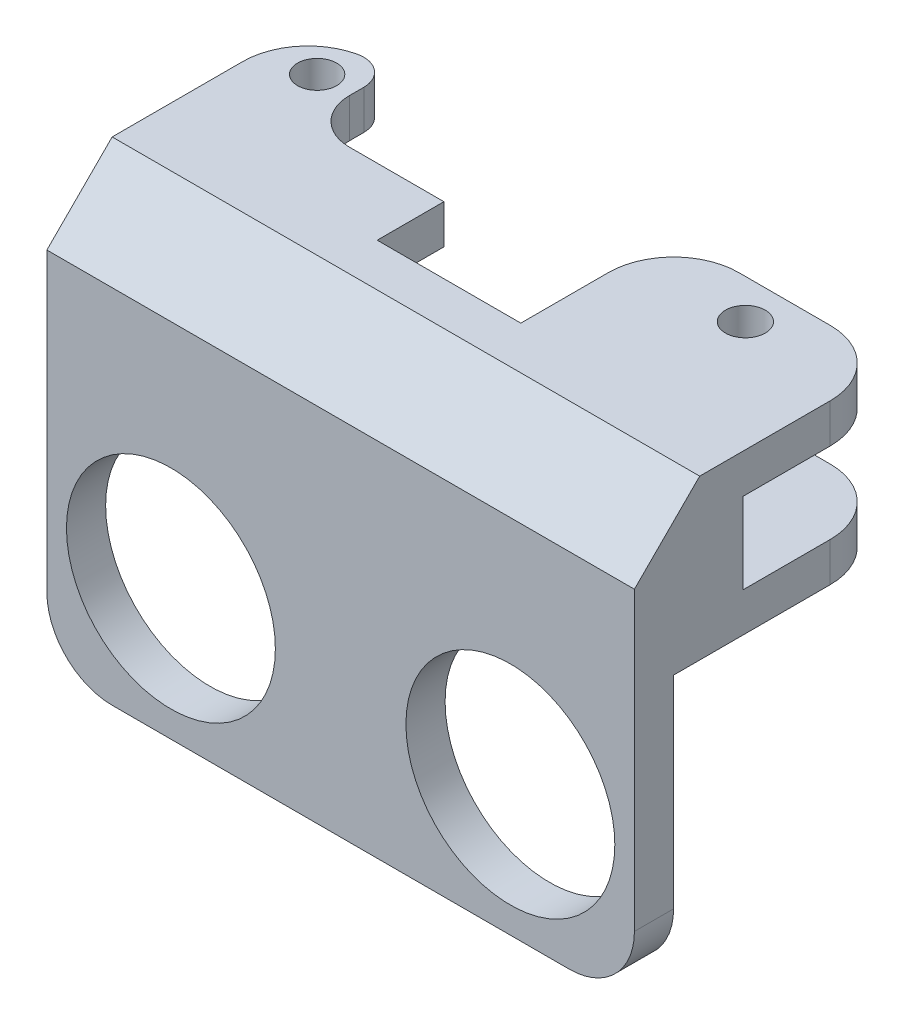
SolidWorks part; units mm, degrees
ref_plane "Front Plane" through (0, 0, 0) normal (0, 0, 1) x (1, 0, 0)
ref_plane "Top Plane" through (0, 0, 0) normal (0, 1, 0) x (1, 0, 0)
ref_plane "Right Plane" through (0, 0, 0) normal (1, 0, 0) x (0, 0, -1)
sketch "Sketch1" plane through (0, 0, 0) normal (0, 0, 1) x (1, 0, 0)
  line L0 (-17.5, -10.5) -> (17.5, -10.5)
  line L1 (22.5, -5.5) -> (22.5, 10.5)
  line L3 (-22.5, 10.5) -> (-22.5, -5.5)
  line L6 (-22.5, 10.5) -> (-22.5, 13)
  line L7 (-22.5, 13) -> (22.5, 13)
  line L8 (22.5, 10.5) -> (22.5, 13)
  circle A0 centre (13, -0.5) radius 8
  circle A1 centre (-13, -0.5) radius 8
  arc A2 (17.5, -10.5) -> (22.5, -5.5) centre (17.5, -5.5) ccw
  arc A3 (-22.5, -5.5) -> (-17.5, -10.5) centre (-17.5, -5.5) ccw
  dimension "D1" = 35
extrude "Boss-Extrude1" add sketch "Sketch1" along normal blind 3
sketch "Sketch2" plane through (0, 0, 0) normal (0, 0, -1) x (-1, 0, 0)
  line L0 (22.5, 13) -> (22.5, -5.5) construction
  line L1 (-22.5, 13) -> (22.5, 13)
  line L2 (-22.5, 13) -> (-22.5, 10)
  line L3 (-22.5, 10) -> (22.5, 10)
  line L4 (22.5, 13) -> (22.5, 10)
  line L6 (-5.5, 13) -> (5.5, 13)
  line L7 (-5.5, 13) -> (-5.5, 10)
  line L8 (-5.5, 10) -> (5.5, 10)
  line L9 (5.5, 13) -> (5.5, 10)
  point P11 (0, 10)
  point P12 (0, 10)
  line M6 (22.5, -5.5) -> (22.5, 13)
  line M7 (22.5, 13) -> (-22.5, 13)
  line M8 (-22.5, 13) -> (-22.5, -5.5)
  dimension "D1" = 3
  dimension "D2" = 11
extrude "Boss-Extrude2" add sketch "Sketch2" along normal blind 17 contours L7 L3 M7 M8 | L9 L3 M7 M6
sketch "Sketch3" plane through (0, 13, 0) normal (0, 1, 0) x (1, 0, 0)
  line L0 (22.5, -3) -> (22.5, 17) construction
  line L1 (-22.5, -3) -> (22.5, -3)
  line L2 (-22.5, -3) -> (-22.5, 0)
  line L3 (-22.5, 0) -> (22.5, 0)
  line L4 (22.5, -3) -> (22.5, 0)
extrude "Boss-Extrude3" add sketch "Sketch3" along normal blind 9.2
sketch "Sketch4" plane through (-5.5, 0, 0) normal (1, 0, 0) x (0, 0, -1)
  line L0 (17, 10) -> (0, 10) construction
  line L1 (0, 13) -> (5.3, 13)
  line L2 (0, 13) -> (0, 10)
  line L3 (0, 10) -> (5.3, 10)
  line L4 (5.3, 13) -> (5.3, 10)
  dimension "D1" = 5.3
extrude "Boss-Extrude4" add sketch "Sketch4" along normal up to next
sketch "Sketch6" plane through (0, 13, 0) normal (0, 1, 0) x (1, 0, 0)
  line L0 (22.5, 0) -> (22.5, 17) construction
  line L1 (-22.5, 0) -> (22.5, 0)
  line L2 (-22.5, 0) -> (-22.5, 5.3)
  line L3 (-22.5, 5.3) -> (22.5, 5.3)
  line L4 (22.5, 0) -> (22.5, 5.3)
extrude "Boss-Extrude5" add sketch "Sketch6" along normal up to surface (9.2 mm away) contours L2 L1 L4 L3 up to face at (0, 22.2, 1.5)
sketch "Sketch7" plane through (0, 0, -5.3) normal (0, 0, -1) x (-1, 0, 0)
  line L0 (22.5, 22.2) -> (22.5, 13) construction
  line L1 (-22.5, 22.2) -> (-5.5, 22.2)
  line L2 (-22.5, 22.2) -> (-22.5, 19.2)
  line L3 (-22.5, 19.2) -> (-5.5, 19.2)
  line L4 (22.5, 22.2) -> (22.5, 19.2)
  line L5 (5.5, 22.2) -> (22.5, 22.2)
  line L7 (-5.5, 19.2) -> (-5.5, 22.2)
  line L9 (5.5, 19.2) -> (5.5, 22.2)
  line L10 (5.5, 19.2) -> (22.5, 19.2)
  dimension "D1" = 3
extrude "Boss-Extrude6" add sketch "Sketch7" along normal through all
sketch "Sketch8" plane through (0, 22.2, 0) normal (0, 1, 0) x (1, 0, 0)
  line L0 (5.5, 17) -> (22.5, 17) construction
  line L1 (5.5, 17) -> (5.5, 5.3) construction
  line L2 (0, -11) -> (0, 11) construction
  circle A0 centre (14, 14) radius 1.525
  circle A1 centre (-14, 14) radius 1.525
  dimension "D2" = 3.05
  dimension "D1" = 3
  dimension "D3" = 8.5
extrude "Cut-Extrude1" cut sketch "Sketch8" against normal through all
chamfer "Chamfer1" distance 5 angle 45 1 edges at (0, 22.2, 3)
fillet "Fillet1" radius 5 8 edges at (22.5, 20.7, -17) (5.5, 20.7, -17) (-22.5, 20.7, -17) (-5.5, 20.7, -17) (5.5, 11.5, -17) (22.5, 11.5, -17) (-5.5, 11.5, -17) (-22.5, 11.5, -17)
sketch "Sketch9" plane through (0, 22.2, 0) normal (0, 1, 0) x (1, 0, 0)
  line L0 (-5.5, 10.41) -> (-12.3495, 10.41)
  line L1 (-16.1561, 17) -> (-16.1561, 13.8342)
  line L2 (-12.8495, 10.41) -> (-12.3495, 10.41)
  line L3 (5.5, 5.3) -> (-5.5, 5.3) construction
  line L4 (-5.5, 12) -> (-5.5, 5.3) construction
  line L5 (-17.5, 17) -> (-10.5, 17) construction
  line L14 (-10.5, 17) -> (-17.5, 17)
  line L15 (-22.5, 12) -> (-22.5, 2)
  line L16 (-22.5, 2) -> (22.5, 2)
  line L17 (22.5, 2) -> (22.5, 12)
  line L18 (17.5, 17) -> (10.5, 17)
  line L19 (5.5, 12) -> (5.5, 5.3)
  line L20 (5.5, 5.3) -> (-5.5, 5.3)
  line L21 (-5.5, 5.3) -> (-5.5, 12)
  line L22 (-10.5, 17) -> (-16.1561, 17)
  line L29 (-5.5, 10.41) -> (-5.5, 12)
  arc A0 (-16.1561, 13.8342) -> (-12.8495, 10.41) centre (-12.7298, 13.8342) ccw
  circle A1 centre (-18.8, 14) radius 1.5
  circle A3 centre (-14, 14) radius 1.525
  arc A7 (-17.5, 17) -> (-22.5, 12) centre (-17.5, 12) ccw
  arc A8 (22.5, 12) -> (17.5, 17) centre (17.5, 12) ccw
  arc A9 (10.5, 17) -> (5.5, 12) centre (10.5, 12) ccw
  arc A10 (-5.5, 12) -> (-10.5, 17) centre (-10.5, 12) ccw
  arc A14 (-5.5, 12) -> (-10.5, 17) centre (-10.5, 12) ccw
  point P26 (0, 0)
  point P28 (-18.8038, 14)
  dimension "D2" = 3
  dimension "D1" = 5.11
  dimension "D4" = 4.8
  dimension "D3" = 0
extrude "Cut-Extrude2" cut sketch "Sketch9" against normal through all
fillet "Fillet2" radius 2 2 edges at (-16.1561, 20.7, -17) (-16.1561, 11.5, -17)
